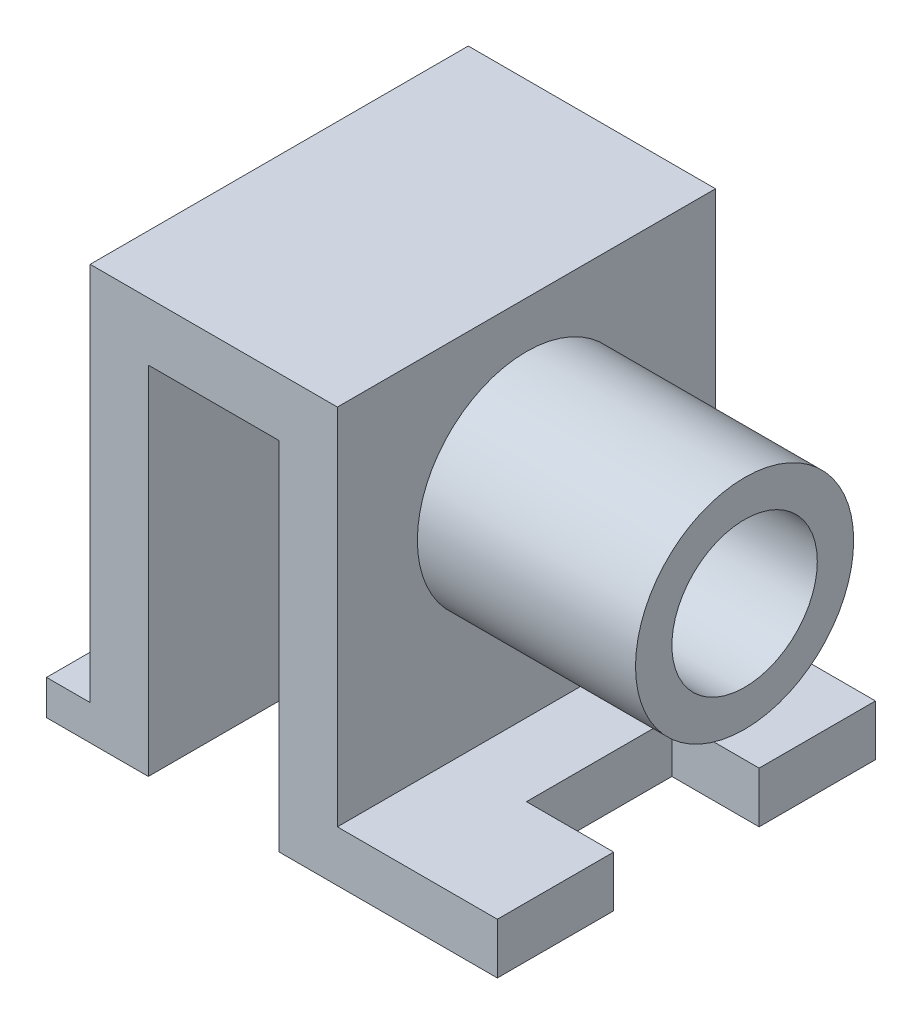
SolidWorks part; units mm, degrees
ref_plane "Front Plane" through (0, 0, 0) normal (0, 0, 1) x (1, 0, 0)
ref_plane "Top Plane" through (0, 0, 0) normal (0, 1, 0) x (1, 0, 0)
ref_plane "Right Plane" through (0, 0, 0) normal (1, 0, 0) x (0, 0, -1)
sketch "Croquis1" plane through (0, 0, 0) normal (0, 0, 1) x (1, 0, 0)
  line L0 (0, 0) -> (14, 0)
  line L1 (14, 0) -> (14, 49)
  line L2 (14, 49) -> (32, 49)
  line L3 (32, 49) -> (32, 0)
  line L4 (32, 0) -> (62, 0)
  line L5 (62, 0) -> (62, 7)
  line L6 (62, 7) -> (40, 7)
  line L7 (40, 7) -> (40, 57)
  line L8 (40, 57) -> (6, 57)
  line L9 (6, 57) -> (6, 4.8045)
  line L10 (6, 4.8045) -> (0, 4.8045)
  line L11 (0, 4.8045) -> (0, 0)
  point P12 (0, 0)
  point P14 (0, 0)
  dimension "D1" = 18
  dimension "D2" = 62
  dimension "D3" = 8
  dimension "D4" = 7
  dimension "D5" = 22
  dimension "D6" = 34
  dimension "D7" = 8
  dimension "D8" = 57
extrude "Saliente-Extruir2" add sketch "Croquis1" along normal mid plane 52
sketch "Croquis3" plane through (0, 7, 0) normal (0, 1, 0) x (1, 0, 0)
  line L0 (62, 0) -> (62, 10)
  line L1 (62, -26) -> (62, 26) construction
  line L2 (62, 10) -> (50, 10)
  line L3 (50, 10) -> (50, -10)
  line L4 (50, -10) -> (62, -10)
  line L5 (62, -10) -> (62, 0)
  line L6 (62, 26) -> (40, 26) construction
  line L7 (62, -26) -> (40, -26) construction
  dimension "D1" = 16
  dimension "D2" = 16
  dimension "D3" = 12
extrude "Cortar-Extruir1" cut sketch "Croquis3" against normal through all
sketch "Croquis4" plane through (40, 0, 0) normal (1, 0, 0) x (0, 0, -1)
  line L0 (0, 57) -> (0, 14.2199) construction
  line L1 (-26, 57) -> (26, 57) construction
  circle A0 centre (0, 35.6099) radius 15
  circle A1 centre (0, 35.6099) radius 10
  dimension "D1" = 30
extrude "Saliente-Extruir3" add sketch "Croquis4" along normal blind 30
